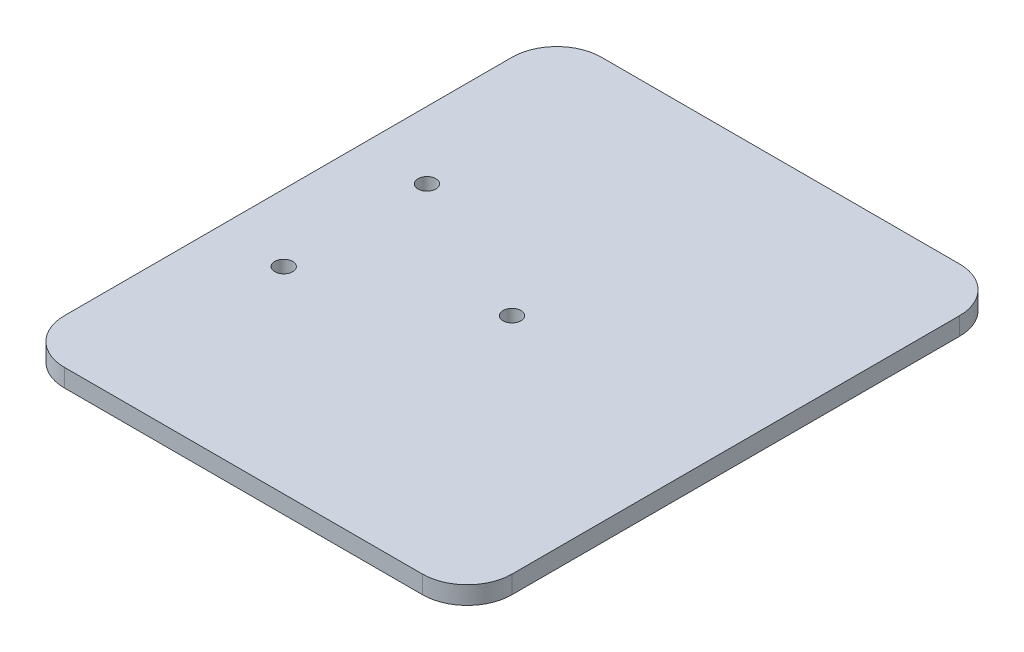
SolidWorks part; units mm, degrees
ref_plane "Front Plane" through (0, 0, 0) normal (0, 0, 1) x (1, 0, 0)
ref_plane "Top Plane" through (0, 0, 0) normal (0, 1, 0) x (1, 0, 0)
ref_plane "Right Plane" through (0, 0, 0) normal (1, 0, 0) x (0, 0, -1)
sketch "Sketch1" plane through (0, 0, 0) normal (0, 1, 0) x (1, 0, 0)
  line L1 (-41.4151, 11.8868) -> (-1.4151, 11.8868)
  line L2 (-46.4151, 6.8868) -> (-46.4151, -43.1132)
  line L3 (-41.4151, -48.1132) -> (-1.4151, -48.1132)
  line L4 (3.5849, 6.8868) -> (3.5849, -43.1132)
  arc A0 (-1.4151, 11.8868) -> (3.5849, 6.8868) centre (-1.4151, 6.8868) cw
  arc A1 (-1.4151, -48.1132) -> (3.5849, -43.1132) centre (-1.4151, -43.1132) ccw
  arc A2 (-46.4151, -43.1132) -> (-41.4151, -48.1132) centre (-41.4151, -43.1132) ccw
  arc A3 (-41.4151, 11.8868) -> (-46.4151, 6.8868) centre (-41.4151, 6.8868) ccw
  point P6 (3.5849, 11.8868)
  point P11 (-46.4151, -48.1132)
  point P14 (-46.4151, 11.8868)
  dimension "D3" = 5
  dimension "D1" = 60
  dimension "D2" = 50
extrude "Boss-Extrude1" add sketch "Sketch1" along normal blind 2
sketch "Sketch2" plane through (0, 2, 0) normal (0, 1, 0) x (1, 0, 0)
  line L0 (-1.4151, 11.8868) -> (-41.4151, 11.8868) construction
  line L1 (-41.4151, -48.1132) -> (-1.4151, -48.1132) construction
  line L2 (-46.4151, 6.8868) -> (-46.4151, -43.1132) construction
  line L3 (3.5849, -43.1132) -> (3.5849, 6.8868) construction
  circle A0 centre (-38.9151, -10.1132) radius 1
  circle A1 centre (-38.9151, -26.1132) radius 1
  circle A2 centre (-21.4151, -18.1132) radius 1
  point P12 (0, 0)
  dimension "D1" = 22
  dimension "D2" = 22
  dimension "D5" = 30
  dimension "D3" = 7.5
  dimension "D4" = 7.5
  dimension "D6" = 25
extrude "Cut-Extrude1" cut sketch "Sketch2" against normal blind 2
